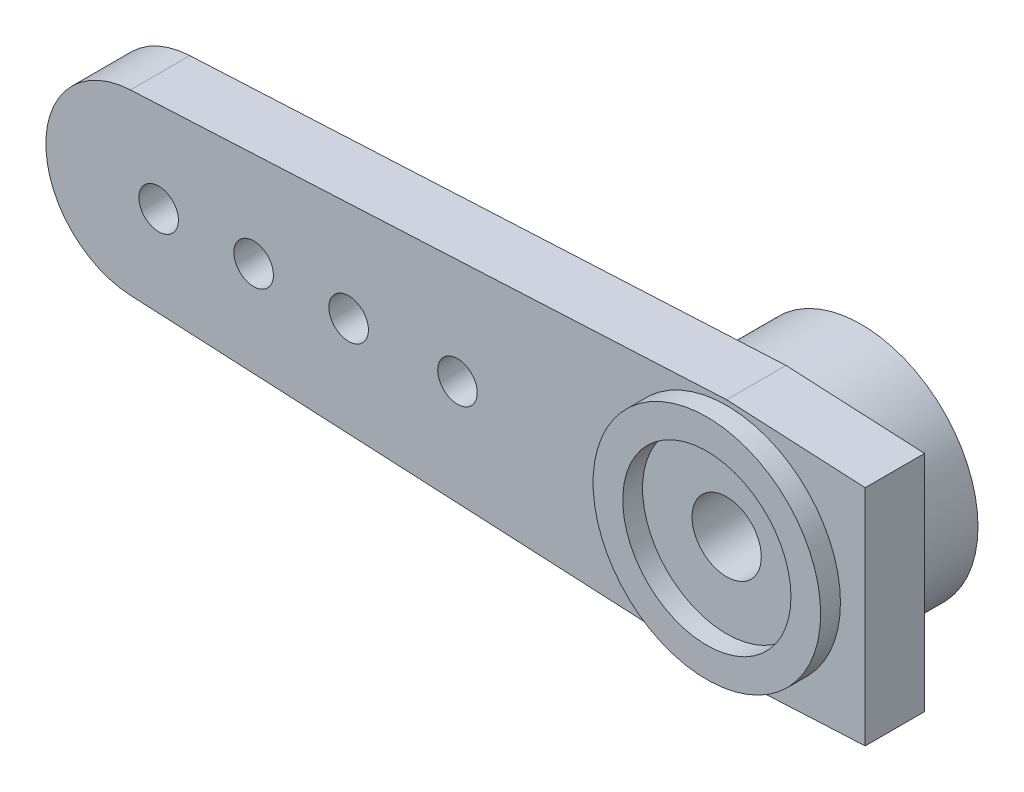
SolidWorks part; units mm, degrees
ref_plane "Front" through (0, 0, 0) normal (0, 0, 1) x (1, 0, 0)
ref_plane "Top" through (0, 0, 0) normal (0, 1, 0) x (1, 0, 0)
ref_plane "Right" through (0, 0, 0) normal (1, 0, 0) x (0, 0, -1)
sketch "Sketch1" plane through (0, 0, 0) normal (0, 0, 1) x (1, 0, 0)
  circle A0 centre (0, 0) radius 2.25
  circle A1 centre (0, 0) radius 2.95
  dimension "D1" = 5.9
  dimension "D2" = 0.7
extrude "Boss-Extrude1" add sketch "Sketch1" along normal blind 1.9
sketch "Sketch2" plane through (0, 0, 1.9) normal (0, 0, 1) x (1, 0, 0)
  line L0 (0, 0) -> (0, 2.95) construction
  line L1 (15.0623, 2.2472) -> (0, 3)
  line L2 (0, 0) -> (14.95, 0) construction
  line L3 (-15.0623, 2.2472) -> (0, 3)
  line L4 (-15.0623, -2.2472) -> (0, -3)
  line L5 (15.0623, -2.2472) -> (0, -3)
  arc A0 (-15.0623, -2.2472) -> (-15.0623, 2.2472) centre (-14.95, 0) cw
  arc A1 (15.0623, -2.2472) -> (15.0623, 2.2472) centre (14.95, 0) ccw
  circle A2 centre (0, 0) radius 2.95 construction
  circle A3 centre (0, 0) radius 0.875
  circle A4 centre (6.8, 0) radius 0.5
  circle A5 centre (9.55, 0) radius 0.5
  circle A6 centre (11.95, 0) radius 0.5
  circle A7 centre (14.35, 0) radius 0.5
  circle A8 centre (-14.35, 0) radius 0.5
  circle A9 centre (-11.95, 0) radius 0.5
  circle A10 centre (-9.55, 0) radius 0.5
  circle A11 centre (-6.8, 0) radius 0.5
  dimension "D1" = 3
  dimension "D2" = 2.25
  dimension "D3" = 29.9
  dimension "D4" = 1.75
  dimension "D5" = 1
  dimension "D6" = 2.75
  dimension "D7" = 2.4
  dimension "D8" = 2.4
  dimension "D9" = 13.6
extrude "Boss-Extrude2" add sketch "Sketch2" along normal blind 1.5
sketch "Sketch3" plane through (0, 0, 3.4) normal (0, 0, 1) x (1, 0, 0)
  circle A0 centre (0, 0) radius 2.875
  circle A1 centre (0, 0) radius 2.125
  dimension "D1" = 5.75
  dimension "D2" = 0.75
extrude "Boss-Extrude3" add sketch "Sketch3" along normal blind 0.5
sketch "Sketch4" plane through (0, 0, 3.4) normal (0, 0, 1) x (1, 0, 0)
  line L0 (3.5, 2.8251) -> (3.5, -2.8251)
  line L1 (15.0623, 2.2472) -> (0, 3) construction
  line L2 (0, -3) -> (15.0623, -2.2472) construction
  line L7 (15.0623, 2.2472) -> (0, 3)
  line L8 (0, 3) -> (-15.0623, 2.2472)
  line L9 (-15.0623, -2.2472) -> (0, -3)
  line L10 (0, -3) -> (15.0623, -2.2472)
  line L11 (15.0623, 2.2472) -> (3.5, 2.8251)
  line L14 (3.5, -2.8251) -> (15.0623, -2.2472)
  arc A2 (15.0623, -2.2472) -> (15.0623, 2.2472) centre (14.95, 0) ccw
  arc A3 (-15.0623, 2.2472) -> (-15.0623, -2.2472) centre (-14.95, 0) ccw
  arc A4 (15.0623, -2.2472) -> (15.0623, 2.2472) centre (14.95, 0) ccw
  dimension "D2" = 3.5
  dimension "D1" = 0
extrude "Cut-Extrude1" cut sketch "Sketch4" against normal blind 10
